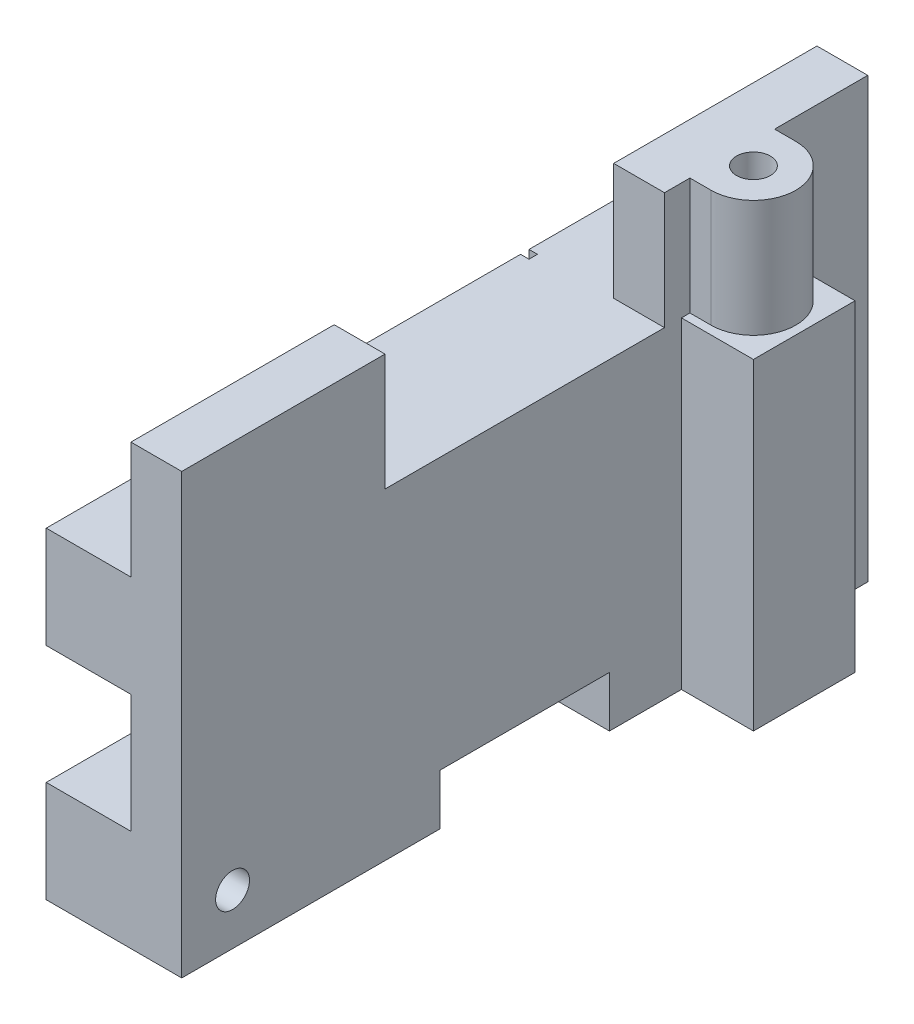
SolidWorks part; units mm, degrees
ref_plane "前视基准面" through (0, 0, 0) normal (0, 0, 1) x (1, 0, 0)
ref_plane "上视基准面" through (0, 0, 0) normal (0, 1, 0) x (1, 0, 0)
ref_plane "右视基准面" through (0, 0, 0) normal (1, 0, 0) x (0, 0, -1)
other "Configuration Table"
sketch "草图1" plane through (0, 0, 0) normal (0, 0, 1) x (1, 0, 0)
  line L8 (3, -13) -> (-5, -13)
  line L9 (-5, -13) -> (-5, -7)
  line L10 (-5, -7) -> (0, -7)
  line L11 (0, -7) -> (0, 0)
  line L12 (0, 0) -> (-5, 0)
  line L13 (-5, 0) -> (-5, 6)
  line L16 (3, 6) -> (3, -13)
  line L17 (-5, 6) -> (3, 6)
  point P0 (-5, -7.402)
  point P1 (-5, 3)
  dimension "D1" = 8
  dimension "D2" = 5
  dimension "D3" = 6
  dimension "D6" = 7
  dimension "D7" = 6
extrude "凸台-拉伸1" add sketch "草图1" along normal blind 40.5
sketch "草图2" plane through (0, 6, 0) normal (0, 1, 0) x (1, 0, 0)
  line L0 (3, 0) -> (-5, 0) construction
  line L6 (0, -13.7584) -> (0, -50013.7584) construction
  line L7 (-9.223, -8) -> (49990.777, -8) construction
  line L8 (4.25, -19.1724) -> (4.25, -50019.1724) construction
  line L9 (-5, -40.5) -> (-5, 0) construction
  line L15 (3, -11) -> (7.25, -11)
  line L16 (3, -40.5) -> (3, 0) construction
  line L17 (7.25, -11) -> (7.25, -5)
  line L18 (7.25, -5) -> (3, -5)
  line L19 (3, -5) -> (3, -11)
  circle A0 centre (4.25, -8) radius 1
  point P0 (4.25, -8)
  dimension "D1" = 2
  dimension "D2" = 6
  dimension "D3" = 3
  dimension "D4" = 5
  dimension "D5" = 1.25
  dimension "D6" = 8
  dimension "D7" = 3
extrude "凸台-拉伸2" add sketch "草图2" against normal blind 19
sketch "草图6" plane through (0, 6, 0) normal (0, 1, 0) x (1, 0, 0)
  line L0 (3, -40.5) -> (3, -11) construction
  line L5 (0, -40.5) -> (3, -40.5)
  line L6 (0, -40.5) -> (0, -28.5)
  line L7 (0, -28.5) -> (3, -28.5)
  line L8 (3, -40.5) -> (3, -28.5)
  line L9 (4.25, -10.5) -> (3, -10.5)
  line L10 (0, 0) -> (3, 0)
  line L11 (0, 0) -> (0, -12)
  line L12 (0, -12) -> (3, -12)
  line L13 (3, 0) -> (3, -5.5)
  line L14 (4.25, -5.5) -> (3, -5.5)
  line L15 (3, -10.5) -> (3, -12)
  circle A0 centre (4.25, -8) radius 1
  arc A1 (4.25, -10.5) -> (4.25, -5.5) centre (4.25, -8) ccw
  dimension "D1" = 5
  dimension "D2" = 2
  dimension "D3" = 12
  dimension "D4" = 12
extrude "凸台-拉伸3" add sketch "草图6" along normal blind 6.9
sketch "草图7" plane through (3, 0, 0) normal (1, 0, 0) x (0, 0, -1)
  line L2 (-20.25, 10.6197) -> (-20.25, -49989.3803) construction
  line L3 (-40.5, -13) -> (-40.5, 12.9) construction
  line L4 (-40.5, -13) -> (-11, -13) construction
  line L5 (-25.25, -10) -> (-15.25, -10)
  line L6 (-25.25, -10) -> (-25.25, -13)
  line L7 (-25.25, -13) -> (-15.25, -13)
  line L8 (-15.25, -10) -> (-15.25, -13)
  line L9 (-25.25, -10) -> (-15.25, -13) construction
  line L10 (-25.25, -13) -> (-15.25, -10) construction
  point P2 (-20.25, -11.5)
  dimension "D1" = 20.25
  dimension "D2" = 10
  dimension "3" = 3
extrude "切除-拉伸1" cut sketch "草图7" against normal blind 4
sketch "草图9" plane through (-5, 0, 0) normal (-1, 0, 0) x (0, 0, 1)
  line L0 (40.5, -10) -> (-49959.5, -10) construction
  line L1 (40.5, -7) -> (40.5, -13) construction
  line L2 (0, -7) -> (0, -13) construction
  circle A0 centre (37.5, -10) radius 2
  circle A1 centre (3, -10) radius 2
  point P4 (40.5, -10)
  dimension "D1" = 4
  dimension "D4" = 4
  dimension "D2" = 3
  dimension "D3" = 3
extrude "切除-拉伸2" cut sketch "草图9" against normal blind 2
sketch "草图10" plane through (-3, 0, 0) normal (-1, 0, 0) x (0, 0, 1)
  circle A0 centre (37.5, -10) radius 1
  circle A1 centre (3, -10) radius 1
  dimension "D1" = 2
  dimension "D2" = 2
extrude "切除-拉伸3" cut sketch "草图10" against normal blind 12
sketch "草图12" plane through (-5, 0, 0) normal (-1, 0, 0) x (0, 0, 1)
  line L0 (40.5, -13) -> (0, -13) construction
  line L1 (12, 6) -> (12.5, 6)
  line L2 (12, 6) -> (12, -13)
  line L3 (12, -13) -> (12.5, -13)
  line L4 (12.5, 6) -> (12.5, -13)
  line L6 (28.5, 6) -> (28, 6)
  line L7 (28.5, 6) -> (28.5, -13)
  line L8 (28.5, -13) -> (28, -13)
  line L9 (28, 6) -> (28, -13)
  dimension "D1" = 0.5
  dimension "D2" = 0.5
extrude "切除-拉伸4" cut sketch "草图12" against normal blind 0.5
